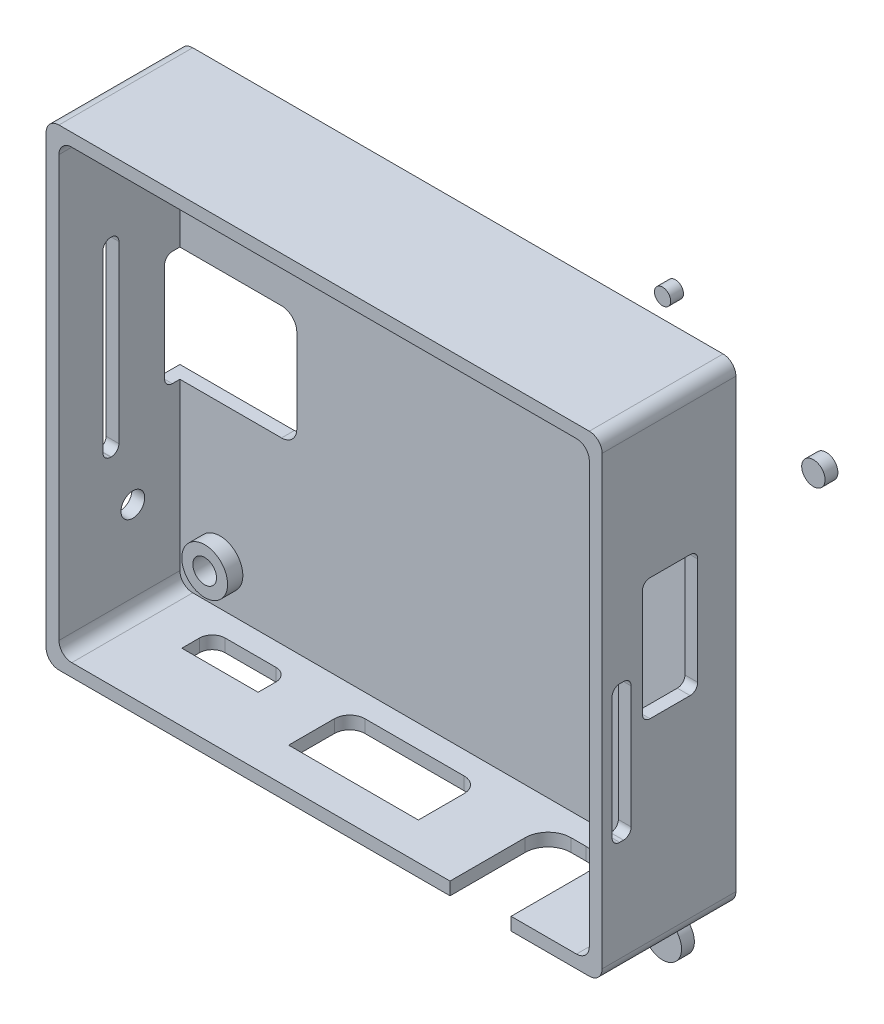
SolidWorks part; units mm, degrees
ref_plane "前视基准面" through (0, 0, 0) normal (0, 0, 1) x (1, 0, 0)
ref_plane "上视基准面" through (0, 0, 0) normal (0, 1, 0) x (1, 0, 0)
ref_plane "右视基准面" through (0, 0, 0) normal (1, 0, 0) x (0, 0, -1)
sketch "草图1" plane through (0, 0, 0) normal (0, 0, 1) x (1, 0, 0)
  line L1 (-76.2588, 51.6727) -> (-18.2588, 51.6727) construction
  line L2 (-76.2588, 51.6727) -> (-76.2588, 2.6727) construction
  line L3 (-76.2588, 2.6727) -> (-18.2588, 2.6727) construction
  line L4 (-18.2588, 51.6727) -> (-18.2588, 2.6727) construction
  line L5 (-76.2588, 51.6727) -> (-18.2588, 2.6727) construction
  line L6 (-76.2588, 2.6727) -> (-18.2588, 51.6727) construction
  line L7 (-80.5088, 55.9227) -> (-14.0088, 55.9227) construction
  line L8 (-80.5088, 55.9227) -> (-80.5088, -1.5773) construction
  line L9 (-80.5088, -1.5773) -> (-14.0088, -1.5773) construction
  line L10 (-14.0088, 55.9227) -> (-14.0088, -1.5773) construction
  line L11 (-80.5088, 55.9227) -> (-14.0088, -1.5773) construction
  line L12 (-80.5088, -1.5773) -> (-14.0088, 55.9227) construction
  line L13 (-83.1888, 57.6027) -> (-10.3288, 57.6027)
  line L14 (-83.1888, 57.6027) -> (-83.1888, -4.2573)
  line L15 (-83.1888, -4.2573) -> (-10.3288, -4.2573)
  line L16 (-10.3288, 57.6027) -> (-10.3288, -4.2573)
  circle A0 centre (-76.2588, 51.6727) radius 1.55
  circle A1 centre (-18.2588, 51.6727) radius 1.55
  circle A2 centre (-76.2588, 2.6727) radius 1.55
  circle A3 centre (-18.2588, 2.6727) radius 1.55
  circle A4 centre (1.5043, 51.6727) radius 1.5315
  circle A5 centre (-18.2588, 61.841) radius 1.0639
  circle A6 centre (-18.2588, -10.9758) radius 2.4893
  point P0 (-47.2588, 27.1727)
  point P9 (-47.2588, 27.1727)
  point P14 (-47.2588, 27.1727)
  dimension "D3" = 57.5
  dimension "D1" = 49
  dimension "D2" = 58
  dimension "D4" = 66.5
  dimension "D5" = 2.68
  dimension "D6" = 3.68
  dimension "D7" = 1.68
  dimension "D8" = 2.68
extrude "凸台-拉伸1" add sketch "草图1" along normal blind 1.68
sketch "草图2" plane through (0, 0, 1.68) normal (0, 0, 1) x (1, 0, 0)
  circle A0 centre (-76.2588, 2.6727) radius 3
  circle A1 centre (-18.2588, 2.6727) radius 3
  circle A2 centre (-76.2588, 51.6727) radius 3
  circle A3 centre (-18.2588, 51.6727) radius 3
  circle A4 centre (-76.2588, 51.6727) radius 1.55
  circle A5 centre (-18.2588, 51.6727) radius 1.55
  circle A6 centre (-76.2588, 2.6727) radius 1.55
  circle A7 centre (-18.2588, 2.6727) radius 1.55
  dimension "D1" = 6
  dimension "D2" = 6
extrude "凸台-拉伸3" add sketch "草图2" along normal blind 2
sketch "草图3" plane through (0, 0, 1.68) normal (0, 0, 1) x (1, 0, 0)
  line L1 (-83.1888, 57.6027) -> (-10.3288, 57.6027)
  line L2 (-83.1888, 57.6027) -> (-83.1888, -4.2573)
  line L3 (-83.1888, -4.2573) -> (-10.3288, -4.2573)
  line L4 (-10.3288, 57.6027) -> (-10.3288, -4.2573)
  line L5 (-12.0075, -2.5773) -> (-81.5088, -2.5773)
  line L6 (-12.0075, -2.5773) -> (-12.0075, 55.9227)
  line L7 (-12.0075, 55.9227) -> (-81.5088, 55.9227)
  line L8 (-81.5088, -2.5773) -> (-81.5088, 55.9227)
  dimension "D1" = 1.68
  dimension "D2" = 1.68
  dimension "D3" = 1.68
  dimension "D4" = 1.6787
extrude "凸台-拉伸4" add sketch "草图3" along normal blind 15.85
sketch "草图4" plane through (0, 0, 0) normal (0, 0, -1) x (-1, 0, 0)
  line L0 (83.1888, 57.6027) -> (83.1888, -4.2573) construction
  line L1 (83.1888, 35.8222) -> (66.1888, 35.8222)
  line L2 (83.1888, 35.8222) -> (83.1888, 20.8222)
  line L3 (83.1888, 20.8222) -> (66.1888, 20.8222)
  line L4 (66.1888, 35.8222) -> (66.1888, 20.8222)
  line L6 (65.1888, 28.3222) -> (75.9896, 28.3222) construction
  line L7 (76.2588, 2.6422) -> (79.1268, 2.6422) construction
  dimension "D1" = 17
  dimension "D2" = 15
  dimension "D3" = 25.68
  dimension "D4" = 7.5
extrude "切除-拉伸1" cut sketch "草图4" against normal blind 3.68
sketch "草图5" plane through (0, 0, 0) normal (0, 0, -1) x (-1, 0, 0)
  circle A0 centre (18.2588, 51.6727) radius 4
  circle A1 centre (18.2588, 2.6727) radius 4
  circle A2 centre (76.2588, 2.6727) radius 4
  circle A3 centre (76.2588, 51.6727) radius 4
sketch "草图6" plane through (-10.3288, 0, 0) normal (1, 0, 0) x (0, 0, -1)
  line L0 (0, -4.2573) -> (0, 57.6027) construction
  line L1 (-5, 38.6727) -> (-12.25, 38.6727)
  line L2 (-5, 38.6727) -> (-5, 22.6727)
  line L3 (-5, 22.6727) -> (-12.25, 22.6727)
  line L4 (-12.25, 38.6727) -> (-12.25, 22.6727)
  line L5 (-8.998, 30.6727) -> (-4.8026, 30.6727) construction
  line L7 (0, 51.6727) -> (-8.3915, 51.6727) construction
  line L8 (-16.2253, 28.6288) -> (-13.7253, 28.6288)
  line L9 (-16.2253, 28.6288) -> (-16.2253, 10.6288)
  line L10 (-16.2253, 10.6288) -> (-13.7253, 10.6288)
  line L11 (-13.7253, 28.6288) -> (-13.7253, 10.6288)
  dimension "D1" = 5
  dimension "D2" = 16
  dimension "D3" = 21
  dimension "D4" = 8
  dimension "D5" = 7.25
  dimension "D6" = 18
  dimension "D8" = 2.5
extrude "切除-拉伸3" cut sketch "草图6" against normal blind 7.8
sketch "草图7" plane through (0, -4.2573, 0) normal (0, -1, 0) x (1, 0, 0)
  line L0 (-83.1888, 0) -> (-10.3288, 0) construction
  line L1 (-74.2588, 8.68) -> (-64.2588, 8.68)
  line L2 (-74.2588, 8.68) -> (-74.2588, 4.68)
  line L3 (-74.2588, 4.68) -> (-64.2588, 4.68)
  line L4 (-64.2588, 8.68) -> (-64.2588, 4.68)
  line L5 (-56.2588, 12.68) -> (-39.2588, 12.68)
  line L6 (-56.2588, 12.68) -> (-56.2588, 4.68)
  line L7 (-56.2588, 4.68) -> (-39.2588, 4.68)
  line L8 (-39.2588, 12.68) -> (-39.2588, 4.68)
  line L9 (-30.2588, 17.9803) -> (-22.2588, 17.9803)
  line L10 (-30.2588, 17.9803) -> (-30.2588, 4.68)
  line L11 (-30.2588, 4.68) -> (-22.2588, 4.68)
  line L12 (-22.2588, 17.9803) -> (-22.2588, 4.68)
  line L13 (-69.2588, 5) -> (-69.2588, 4.0793) construction
  line L15 (-47.7588, 10) -> (-47.7588, 5.4217) construction
  line L16 (-26.2588, 9) -> (-26.2588, 5) construction
  line L18 (-18.2588, 0) -> (-18.2588, 3.0287) construction
  dimension "D1" = 4.68
  dimension "D2" = 4.68
  dimension "D3" = 4.68
  dimension "D4" = 10
  dimension "D5" = 4
  dimension "D6" = 51
  dimension "D7" = 5
  dimension "D8" = 17
  dimension "D9" = 8
  dimension "D10" = 8.5
  dimension "D11" = 29.5
  dimension "D12" = 8
  dimension "D14" = 8
  dimension "D15" = 4
extrude "切除-拉伸5" cut sketch "草图7" against normal blind 2
sketch "草图8" plane through (-83.1888, 0, 0) normal (-1, 0, 0) x (0, 0, 1)
  line L1 (9.6742, 41.4555) -> (11.7617, 41.4555)
  line L2 (9.6742, 41.4555) -> (9.6742, 16.5101)
  line L3 (9.6742, 16.5101) -> (11.7617, 16.5101)
  line L4 (11.7617, 41.4555) -> (11.7617, 16.5101)
  circle A0 centre (7.8439, 9.688) radius 1.5569
extrude "切除-拉伸6" cut sketch "草图8" against normal blind 2
fillet "圆角1" radius 1.68 8 edges at (-10.3288, -4.2573, 8.765) (-12.0075, -2.5773, 9.605) (-12.0075, 55.9227, 9.605) (-10.3288, 57.6027, 8.765) (-83.1888, 57.6027, 8.765) (-81.5088, 55.9227, 9.605) (-81.5088, -2.5773, 9.605) (-83.1888, -4.2573, 8.765)
fillet "圆角2" radius 2 2 edges at (-66.1888, 20.8222, 0.84) (-66.1888, 35.8222, 0.84)
fillet "圆角3" radius 1.68 2 edges at (-64.2588, -3.4173, 4.68) (-74.2588, -3.4173, 4.68)
fillet "圆角4" radius 2 2 edges at (-39.2588, -3.4173, 4.68) (-56.2588, -3.4173, 4.68)
fillet "圆角5" radius 3 2 edges at (-22.2588, -3.4173, 4.68) (-30.2588, -3.4173, 4.68)
fillet "圆角6" radius 1 4 edges at (-11.1681, 28.6288, 16.2253) (-11.1681, 28.6288, 13.7253) (-11.1681, 10.6288, 13.7253) (-11.1681, 10.6288, 16.2253)
fillet "圆角7" radius 1 10 edges at (-11.1681, 38.6727, 12.25) (-11.1681, 38.6727, 5) (-11.1681, 22.6727, 5) (-11.1681, 22.6727, 12.25) (-82.3488, 16.5101, 9.6742) (-82.3488, 16.5101, 11.7617) (-82.3488, 41.4555, 11.7617) (-82.3488, 41.4555, 9.6742) (-82.3488, 20.8222, 3.68) (-82.3488, 35.8222, 3.68)
sketch "草图9" plane through (0, 0, 0) normal (0, 0, -1) x (-1, 0, 0)
  circle A0 centre (18.2588, 51.6727) radius 4
  circle A1 centre (76.2588, 51.6727) radius 4
  circle A2 centre (18.2588, 2.6727) radius 4
  circle A3 centre (76.2588, 2.6727) radius 4
extrude "切除-拉伸7" cut sketch "草图9" against normal blind 0.8
sketch "草图10" plane through (0, 0, 0) normal (0, 0, -1) x (-1, 0, 0)
  line L0 (10.3288, 26.6727) -> (36.436, 26.6727) construction
  line L2 (2.8749, 38.6727) -> (101.2829, 38.6727) construction
  line L3 (101.2829, 38.6727) -> (101.2829, 14.6727) construction
  line L4 (101.2829, 14.6727) -> (-3.1548, 14.6727) construction
  line L6 (18.9927, 41.9227) -> (63.7513, 41.9227)
  line L7 (18.9927, 41.9227) -> (18.9927, 35.4227)
  line L8 (18.9927, 35.4227) -> (63.7513, 35.4227)
  line L9 (63.7513, 41.9227) -> (63.7513, 35.4227)
  line L10 (18.9927, 41.9227) -> (63.7513, 35.4227) construction
  line L11 (18.9927, 35.4227) -> (63.7513, 41.9227) construction
  line L12 (19.1475, 17.9227) -> (63.5964, 17.9227)
  line L13 (19.1475, 17.9227) -> (19.1475, 11.4227)
  line L14 (19.1475, 11.4227) -> (63.5964, 11.4227)
  line L15 (63.5964, 17.9227) -> (63.5964, 11.4227)
  line L16 (19.1475, 17.9227) -> (63.5964, 11.4227) construction
  line L17 (19.1475, 11.4227) -> (63.5964, 17.9227) construction
  point P6 (41.372, 38.6727)
  point P11 (41.372, 14.6727)
  dimension "D1" = 12
  dimension "D2" = 12
  dimension "D3" = 6.5
  dimension "D4" = 6.5
extrude "切除-拉伸8" cut sketch "草图10" against normal blind 0.8
